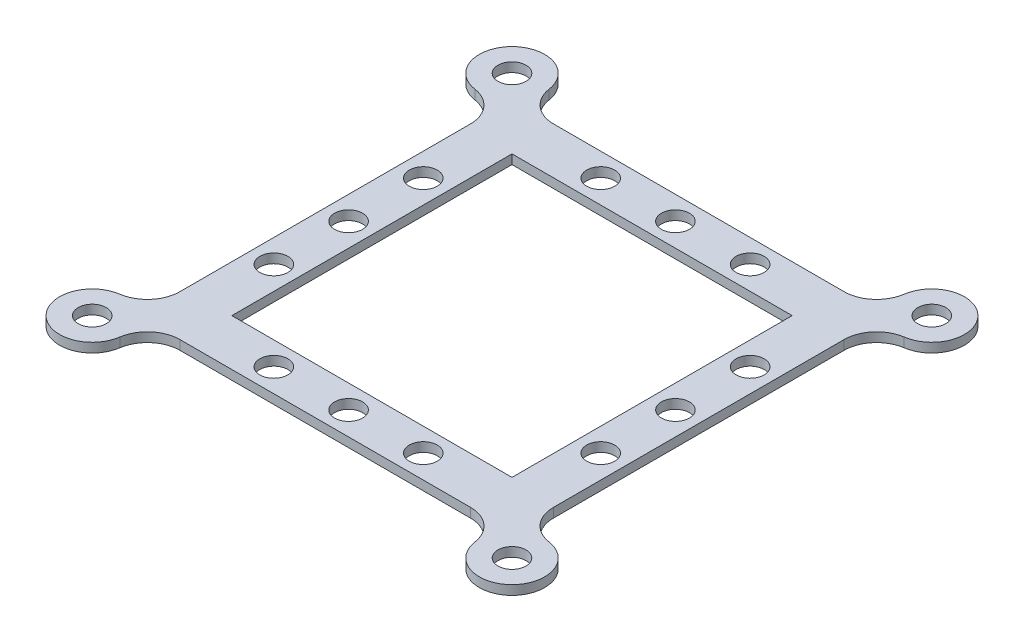
SolidWorks part; units mm, degrees
ref_plane "Alzado" through (0, 0, 0) normal (0, 0, 1) x (1, 0, 0)
ref_plane "Planta" through (0, 0, 0) normal (0, 1, 0) x (1, 0, 0)
ref_plane "Vista lateral" through (0, 0, 0) normal (1, 0, 0) x (0, 0, -1)
sketch "Croquis1" plane through (0, 0, 0) normal (0, 1, 0) x (1, 0, 0)
  line L0 (0, 0) -> (30, 30) construction
  line L1 (0, 0) -> (30, 0)
  line L2 (0, 0) -> (0, 30)
  line L3 (0, 30) -> (30, 30)
  line L4 (30, 0) -> (30, 30)
  line L5 (-5, -5) -> (35, -5)
  line L6 (-5, -5) -> (-5, 30.5503)
  line L7 (-0.5503, 35) -> (35, 35)
  line L8 (35, -5) -> (35, 35)
  line L9 (-5, 35) -> (35, -5) construction
  line L10 (-7.4749, 37.4749) -> (-5, 35) construction
  line L11 (-5, 30.5503) -> (-5, 35) construction
  line L12 (-5, 35) -> (-0.5503, 35) construction
  line L13 (15, 15) -> (0, 15) construction
  line L14 (15, 15) -> (15, 35) construction
  line L15 (30, 15) -> (35, 15) construction
  line L16 (32.5, 15) -> (32.5, 7) construction
  line L17 (32.5, 15) -> (32.5, 23) construction
  circle A0 centre (-7.4749, 37.4749) radius 1.5
  arc A1 (-4.0126, 37.9874) -> (-7.9874, 34.0126) centre (-7.4749, 37.4749) ccw
  arc A2 (-4.0126, 37.9874) -> (-0.5503, 35) centre (-0.5503, 38.5) ccw
  arc A3 (-5, 30.5503) -> (-7.9874, 34.0126) centre (-8.5, 30.5503) ccw
  arc A4 (35, 30.5503) -> (37.9874, 34.0126) centre (38.5, 30.5503) cw
  circle A5 centre (37.4749, 37.4749) radius 1.5
  arc A6 (34.0126, 37.9874) -> (37.9874, 34.0126) centre (37.4749, 37.4749) cw
  arc A7 (34.0126, 37.9874) -> (30.5503, 35) centre (30.5503, 38.5) cw
  arc A8 (34.0126, -7.9874) -> (30.5503, -5) centre (30.5503, -8.5) ccw
  circle A9 centre (37.4749, -7.4749) radius 1.5
  arc A10 (34.0126, -7.9874) -> (37.9874, -4.0126) centre (37.4749, -7.4749) ccw
  arc A11 (35, -0.5503) -> (37.9874, -4.0126) centre (38.5, -0.5503) ccw
  arc A12 (-5, -0.5503) -> (-7.9874, -4.0126) centre (-8.5, -0.5503) cw
  circle A13 centre (-7.4749, -7.4749) radius 1.5
  arc A14 (-4.0126, -7.9874) -> (-7.9874, -4.0126) centre (-7.4749, -7.4749) cw
  arc A15 (-4.0126, -7.9874) -> (-0.5503, -5) centre (-0.5503, -8.5) cw
  circle A16 centre (32.5, 23) radius 1.5
  circle A17 centre (32.5, 7) radius 1.5
  circle A18 centre (23, -2.5) radius 1.5
  circle A19 centre (7, -2.5) radius 1.5
  circle A20 centre (-2.5, 7) radius 1.5
  circle A21 centre (-2.5, 23) radius 1.5
  circle A22 centre (7, 32.5) radius 1.5
  circle A23 centre (23, 32.5) radius 1.5
  circle A24 centre (32.5, 15) radius 1.5
  circle A25 centre (15, -2.5) radius 1.5
  circle A26 centre (-2.5, 15) radius 1.5
  circle A27 centre (15, 32.5) radius 1.5
  point P9 (15, 15)
  point P10 (15, 15)
  point P50 (35, 15)
  dimension "D3" = 3
  dimension "D4" = 2
  dimension "D7" = 3
  dimension "D10" = 3
  dimension "D1" = 30
  dimension "D2" = 40
  dimension "D5" = 3.5
  dimension "D6" = 40
  dimension "D8" = 8
  dimension "D9" = 4
  dimension "D11" = 4
extrude "Saliente-Extruir1" add sketch "Croquis1" along normal blind 1
